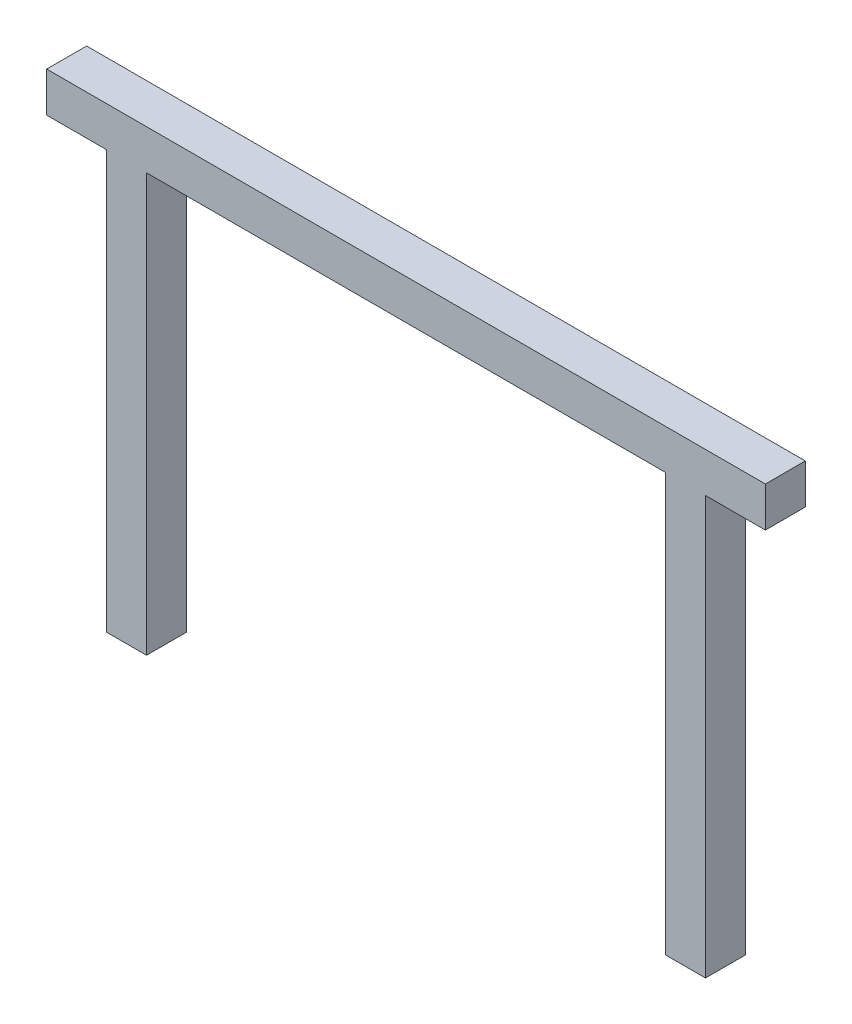
SolidWorks part; units mm, degrees
ref_plane "Front Plane" through (0, 0, 0) normal (0, 0, 1) x (1, 0, 0)
ref_plane "Top Plane" through (0, 0, 0) normal (0, 1, 0) x (1, 0, 0)
ref_plane "Right Plane" through (0, 0, 0) normal (1, 0, 0) x (0, 0, -1)
sketch "Sketch1" plane through (0, 0, 0) normal (0, 0, 1) x (1, 0, 0)
  line L0 (-65, -5) -> (65, -5)
  line L1 (-90, -5) -> (-75, -5)
  line L2 (-90, -5) -> (-90, 5)
  line L3 (-90, 5) -> (90, 5)
  line L4 (90, -5) -> (90, 5)
  line L5 (-90, -5) -> (90, 5) construction
  line L6 (-90, 5) -> (90, -5) construction
  line L7 (-75, -109.6512) -> (-65, -109.6512)
  line L8 (-75, -109.6512) -> (-75, -5)
  line L10 (-65, -109.6512) -> (-65, -5)
  line L11 (-75, -109.6512) -> (-65, -5) construction
  line L12 (-75, -5) -> (-65, -109.6512) construction
  line L13 (65, -109.6512) -> (75, -109.6512)
  line L14 (65, -109.6512) -> (65, -5)
  line L16 (75, -109.6512) -> (75, -5)
  line L17 (65, -109.6512) -> (75, -5) construction
  line L18 (65, -5) -> (75, -109.6512) construction
  line L19 (75, -5) -> (90, -5)
  point P0 (0, 0)
  point P6 (-70, -57.3256)
  point P11 (70, -57.3256)
  dimension "D1" = 180
  dimension "D2" = 10
  dimension "D3" = 10
  dimension "D4" = 10
  dimension "D5" = 15
  dimension "D6" = 15
extrude "Boss-Extrude1" add sketch "Sketch1" along normal blind 10
